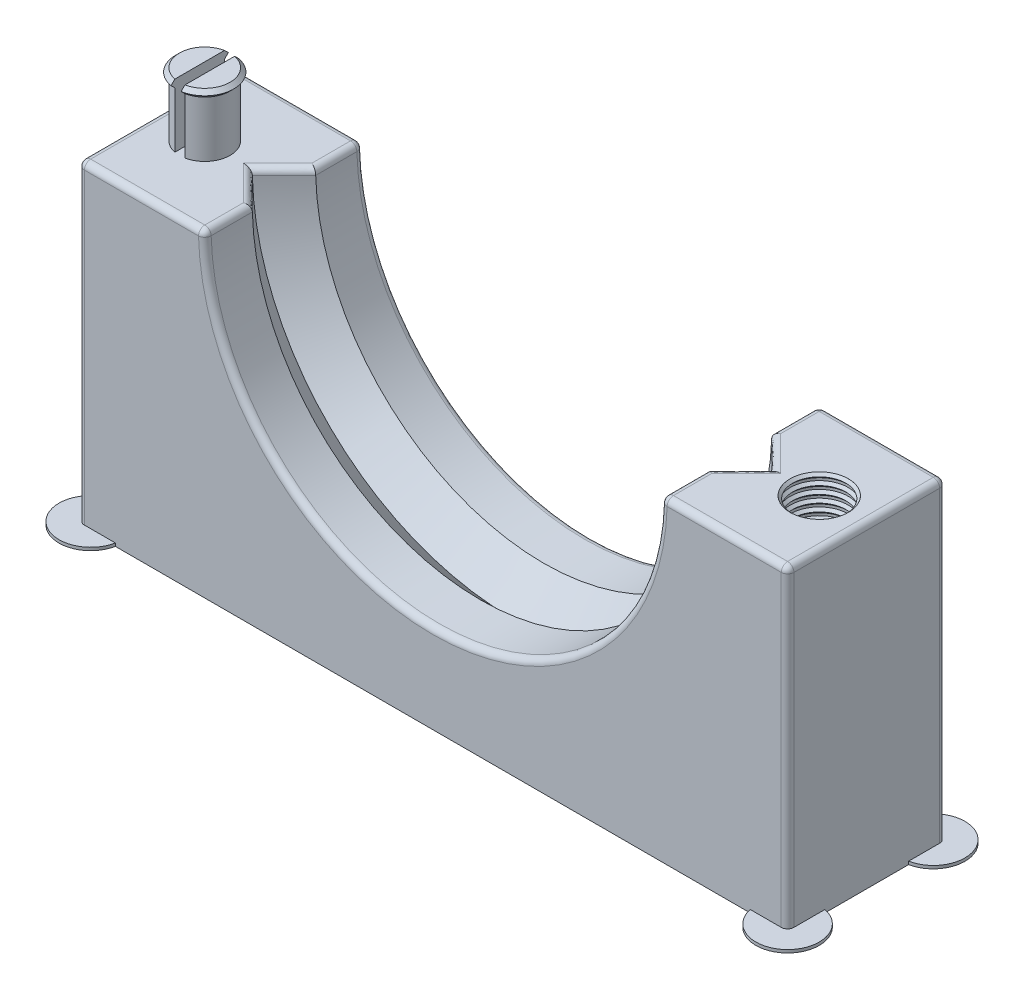
SolidWorks part; units mm, degrees
ref_plane "Front Plane" through (0, 0, 0) normal (0, 0, 1) x (1, 0, 0)
ref_plane "Top Plane" through (0, 0, 0) normal (0, 1, 0) x (1, 0, 0)
ref_plane "Right Plane" through (0, 0, 0) normal (1, 0, 0) x (0, 0, -1)
sketch "Sketch1" plane through (0, 0, 0) normal (0, 0, 1) x (1, 0, 0)
  line L0 (-35.56, 0) -> (35.56, 0)
  line L1 (35.56, 0) -> (35.56, 31.75)
  line L2 (35.56, 31.75) -> (22.86, 31.75)
  line L3 (-22.86, 31.75) -> (-35.56, 31.75)
  line L4 (-35.56, 31.75) -> (-35.56, 0)
  arc A0 (22.86, 31.75) -> (-22.86, 31.75) centre (0, 31.75) cw
  point P7 (0, 0)
  dimension "D2" = 22.86
  dimension "D1" = 31.75
  dimension "D3" = 12.7
extrude "Boss-Extrude1" add sketch "Sketch1" along normal blind 15.875
sketch "Sketch2" plane through (0, 31.75, 0) normal (0, 1, 0) x (1, 0, 0)
  line L0 (22.86, -11.1125) -> (26.035, -7.9375)
  line L2 (22.86, -15.875) -> (22.86, 0) construction
  line L3 (26.035, -7.9375) -> (22.86, -4.7625)
  line L4 (22.8654, -7.9375) -> (35.56, -7.9375) construction
  line L5 (22.86, -4.7625) -> (22.86, -11.1125)
  line L6 (35.56, -15.875) -> (35.56, 0) construction
  line L7 (0, 0) -> (0, -23.6383) construction
  dimension "D1" = 6.35
  dimension "D2" = 3.175
revolve "Cut-Revolve1" cut sketch "Sketch2" angle 360 about L7
sketch "Sketch6" plane through (0, 31.75, 0) normal (0, 1, 0) x (1, 0, 0)
  line L0 (26.035, -7.9375) -> (35.56, -7.9375) construction
  line L1 (35.56, -15.875) -> (35.56, 0) construction
  circle A0 centre (30.7975, -7.9375) radius 2.921
  dimension "D1" = 5.842
extrude "Cut-Extrude2" cut sketch "Sketch6" against normal blind 9.525
sketch "Sketch11" plane through (0, 31.75, 0) normal (0, 1, 0) x (1, 0, 0)
  line L0 (26.035, -7.9375) -> (35.56, -7.9375) construction
  line L1 (35.56, -15.875) -> (35.56, 0) construction
ref_plane "Plane1" through (0, 0, 7.9375) normal (0, 0, 1) x (1, 0, 0)
sketch "Sketch15" plane through (0, 0, 7.9375) normal (0, 0, 1) x (1, 0, 0)
  line L0 (-33.3375, 31.75) -> (-33.3375, 37.338)
  line L1 (-22.86, 31.75) -> (-35.56, 31.75) construction
  line L2 (-33.3375, 37.338) -> (-33.7185, 37.719)
  line L3 (-33.7185, 37.719) -> (-33.3375, 38.1)
  line L4 (-33.3375, 38.1) -> (-30.7975, 38.1)
  line L5 (-30.7975, 38.1) -> (-30.7975, 31.75)
  line L6 (-30.7975, 31.75) -> (-33.3375, 31.75)
  line L7 (-35.56, 31.75) -> (-35.56, 0) construction
  line L8 (-33.3375, 38.1) -> (-33.3375, 37.338) construction
  line L9 (-26.035, 31.75) -> (-35.56, 31.75) construction
  dimension "D1" = 2.54
  dimension "D3" = 6.35
  dimension "D4" = 90
  dimension "D5" = 2.921
revolve "Revolve2" add sketch "Sketch15" angle 360 about L5
sketch "Sketch12" plane through (0, 0, 7.9375) normal (0, 0, 1) x (1, 0, 0)
  line L0 (30.7975, 31.75) -> (30.7975, 26.6144) construction
  line L1 (26.035, 31.75) -> (35.56, 31.75) construction
  line L2 (27.8765, 30.48) -> (28.1305, 30.734)
  line L3 (27.8765, 31.242) -> (28.1305, 31.496)
  line L4 (28.1305, 31.496) -> (27.8765, 31.75)
  line L5 (27.8765, 31.75) -> (27.8765, 31.242)
  line L6 (30.7975, 31.75) -> (27.8765, 31.75) construction
  line L7 (28.1305, 30.734) -> (27.8765, 30.988)
  line L8 (27.8765, 30.988) -> (27.8765, 30.48)
  line L9 (27.8765, 29.718) -> (28.1305, 29.972)
  line L10 (28.1305, 29.972) -> (27.8765, 30.226)
  line L11 (27.8765, 30.226) -> (27.8765, 29.718)
  line L12 (27.8765, 28.956) -> (28.1305, 29.21)
  line L13 (28.1305, 29.21) -> (27.8765, 29.464)
  line L14 (27.8765, 29.464) -> (27.8765, 28.956)
  line L15 (27.8765, 28.194) -> (28.1305, 28.448)
  line L16 (28.1305, 28.448) -> (27.8765, 28.702)
  line L17 (27.8765, 28.702) -> (27.8765, 28.194)
  line L18 (27.8765, 27.432) -> (28.1305, 27.686)
  line L19 (28.1305, 27.686) -> (27.8765, 27.94)
  line L20 (27.8765, 27.94) -> (27.8765, 27.432)
  line L21 (27.8765, 26.67) -> (28.1305, 26.924)
  line L22 (28.1305, 26.924) -> (27.8765, 27.178)
  line L23 (27.8765, 27.178) -> (27.8765, 26.67)
  line L24 (27.8765, 25.908) -> (28.1305, 26.162)
  line L25 (28.1305, 26.162) -> (27.8765, 26.416)
  line L26 (27.8765, 26.416) -> (27.8765, 25.908)
  line L27 (27.8765, 25.146) -> (28.1305, 25.4)
  line L28 (28.1305, 25.4) -> (27.8765, 25.654)
  line L29 (27.8765, 25.654) -> (27.8765, 25.146)
  line L30 (27.8765, 24.384) -> (28.1305, 24.638)
  line L31 (28.1305, 24.638) -> (27.8765, 24.892)
  line L32 (27.8765, 24.892) -> (27.8765, 24.384)
  line L33 (27.8765, 23.622) -> (28.1305, 23.876)
  line L34 (28.1305, 23.876) -> (27.8765, 24.13)
  line L35 (27.8765, 24.13) -> (27.8765, 23.622)
  line L36 (27.8765, 22.86) -> (28.1305, 23.114)
  line L37 (28.1305, 23.114) -> (27.8765, 23.368)
  line L38 (27.8765, 23.368) -> (27.8765, 22.86)
  line L39 (27.8765, 22.098) -> (28.1305, 22.352)
  line L40 (28.1305, 22.352) -> (27.8765, 22.606)
  line L41 (27.8765, 22.606) -> (27.8765, 22.098)
  line L42 (27.8765, 21.336) -> (28.1305, 21.59)
  line L43 (28.1305, 21.59) -> (27.8765, 21.844)
  line L44 (27.8765, 21.844) -> (27.8765, 21.336)
  line L45 (27.8765, 20.574) -> (28.1305, 20.828)
  line L46 (28.1305, 20.828) -> (27.8765, 21.082)
  line L47 (27.8765, 21.082) -> (27.8765, 20.574)
  line L48 (27.8765, 19.812) -> (28.1305, 20.066)
  line L49 (28.1305, 20.066) -> (27.8765, 20.32)
  line L50 (27.8765, 20.32) -> (27.8765, 19.812)
  line L51 (27.8765, 19.05) -> (28.1305, 19.304)
  line L52 (28.1305, 19.304) -> (27.8765, 19.558)
  line L53 (27.8765, 19.558) -> (27.8765, 19.05)
  line L54 (27.8765, 18.288) -> (28.1305, 18.542)
  line L55 (28.1305, 18.542) -> (27.8765, 18.796)
  line L56 (27.8765, 18.796) -> (27.8765, 18.288)
  line L57 (27.8765, 17.526) -> (28.1305, 17.78)
  line L58 (28.1305, 17.78) -> (27.8765, 18.034)
  line L59 (27.8765, 18.034) -> (27.8765, 17.526)
  line L60 (27.8765, 16.764) -> (28.1305, 17.018)
  line L61 (28.1305, 17.018) -> (27.8765, 17.272)
  line L62 (27.8765, 17.272) -> (27.8765, 16.764)
  dimension "D1" = 2.921
  dimension "D2" = 0.508
  dimension "D3" = 90
  dimension "D4" = 20
revolve "Revolve1" add sketch "Sketch12" angle 360 about L0
sketch "Sketch16" plane through (0, 38.1, 0) normal (0, 1, 0) x (1, 0, 0)
  line L1 (-31.3055, -13.5293) -> (-30.2895, -13.5293)
  line L2 (-31.3055, -13.5293) -> (-31.3055, -2.3457)
  line L3 (-31.3055, -2.3457) -> (-30.2895, -2.3457)
  line L4 (-30.2895, -13.5293) -> (-30.2895, -2.3457)
  line L5 (-31.3055, -13.5293) -> (-30.2895, -2.3457) construction
  line L6 (-31.3055, -2.3457) -> (-30.2895, -13.5293) construction
  point P0 (-30.7975, -7.9375)
  dimension "D1" = 1.016
extrude "Cut-Extrude3" cut sketch "Sketch16" against normal up to surface (6.35 mm away) up to face at (-30.7975, 31.75, 10.4775)
fillet "Fillet1" radius 0.635 20 edges at (35.56, 15.875, 0) (35.56, 15.875, 15.875) (0, 8.89, 0) (-22.86, 31.75, 2.3813) (-22.86, 31.75, 13.4937) (22.86, 31.75, 13.4937) (22.86, 31.75, 2.3812) (24.4475, 31.75, 6.35) (24.4475, 31.75, 9.525) (29.21, 31.75, 15.875) (35.56, 31.75, 7.9375) (29.21, 31.75, 0) (-29.21, 31.75, 0) (-24.4475, 31.75, 6.35) (-24.4475, 31.75, 9.525) (0, 8.89, 15.875) (-29.21, 31.75, 15.875) (-35.56, 15.875, 15.875) (-35.56, 31.75, 7.9375) (-35.56, 15.875, 0)
sketch "Sketch17" plane through (0, 0, 0) normal (0, -1, 0) x (-1, 0, 0)
  circle A0 centre (34.925, -15.24) radius 3.175
  circle A1 centre (34.925, -0.635) radius 3.175
  circle A2 centre (-34.925, -0.635) radius 3.175
  circle A3 centre (-34.925, -15.24) radius 3.175
  dimension "D1" = 6.35
  dimension "D2" = 6.35
  dimension "D3" = 6.35
  dimension "D4" = 6.35
extrude "Boss-Extrude2" add sketch "Sketch17" against normal blind 0.3
